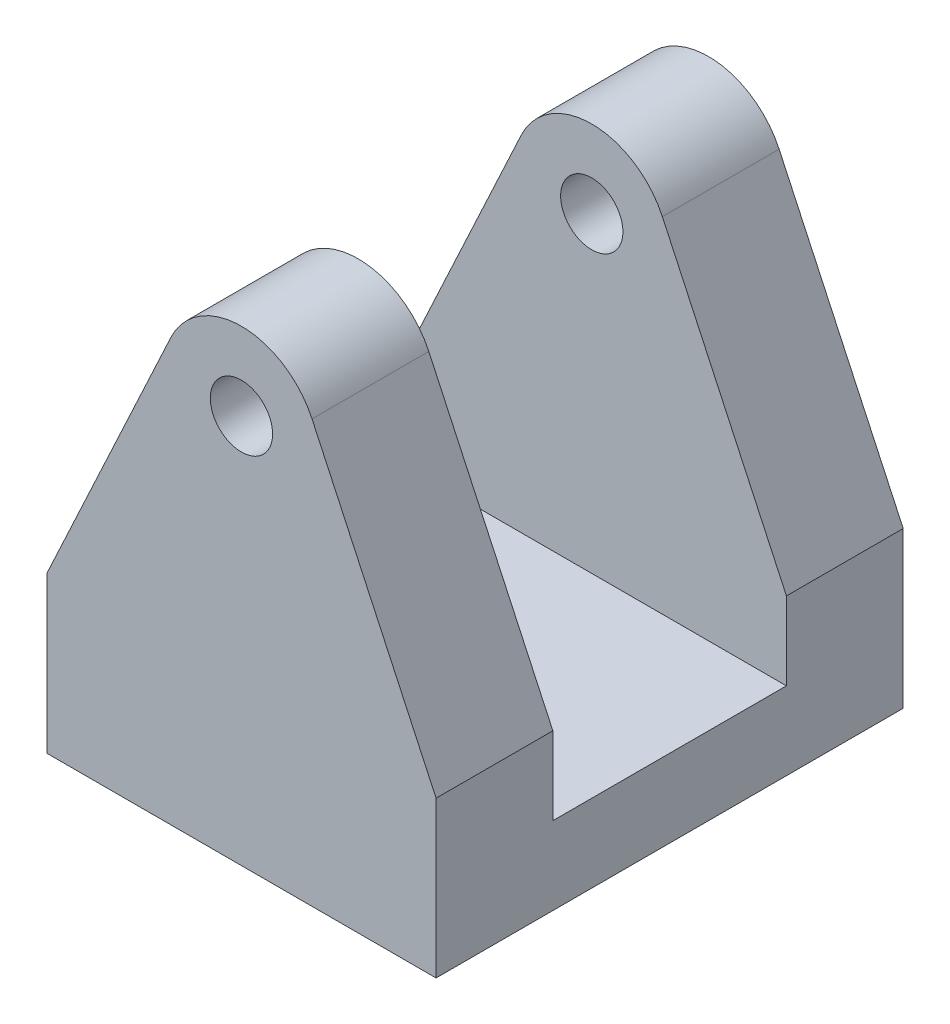
SolidWorks part; units mm, degrees
ref_plane "Front Plane" through (0, 0, 0) normal (0, 0, 1) x (1, 0, 0)
ref_plane "Top Plane" through (0, 0, 0) normal (0, 1, 0) x (1, 0, 0)
ref_plane "Right Plane" through (0, 0, 0) normal (1, 0, 0) x (0, 0, -1)
sketch "Sketch2" plane through (0, 0, 0) normal (0, 0, 1) x (1, 0, 0)
  line L0 (2.4778, -10.0313) -> (2.4778, 15.37)
  line L1 (2.4778, 15.37) -> (22.7158, 58.8333)
  line L2 (45.7432, 58.8333) -> (65.9812, 15.37)
  line L3 (65.9812, 15.37) -> (65.9812, -10.0313)
  line L4 (65.9812, -10.0313) -> (2.4778, -10.0313)
  arc A0 (45.7432, 58.8333) -> (22.7158, 58.8333) centre (34.2295, 53.4721) ccw
  point P9 (34.2295, 83.5601)
  dimension "D4" = 12.7007
  dimension "D1" = 25.4014
  dimension "D2" = 63.5034
  dimension "D3" = 63.5034
extrude "Boss-Extrude2" add sketch "Sketch2" along normal blind 19.05
sketch "Sketch3" plane through (0, 0, 19.05) normal (0, 0, 1) x (1, 0, 0)
  circle A1 centre (34.2295, 53.4721) radius 5.08
  dimension "D1" = 10.16
extrude "Cut-Extrude1" cut sketch "Sketch3" against normal up to surface (19.05 mm away) up to face at (34.2295, 22.6139, 0)
sketch "Sketch5" plane through (0, 0, 0) normal (0, 0, -1) x (-1, 0, 0)
  line L0 (-2.4778, 15.37) -> (-2.4778, -10.0313) construction
  line L1 (-65.9812, -10.0313) -> (-2.4778, -10.0313)
  line L2 (-65.9812, -10.0313) -> (-65.9812, 2.6687)
  line L3 (-65.9812, 2.6687) -> (-2.4778, 2.6687)
  line L4 (-2.4778, -10.0313) -> (-2.4778, 2.6687)
  dimension "D1" = 12.7
extrude "Boss-Extrude3" add sketch "Sketch5" along normal blind 19.05
mirror "Mirror1" about plane through (0, 0, -19.05) normal (0, 0, 1) of "Boss-Extrude3", "Boss-Extrude2", "Cut-Extrude1"
